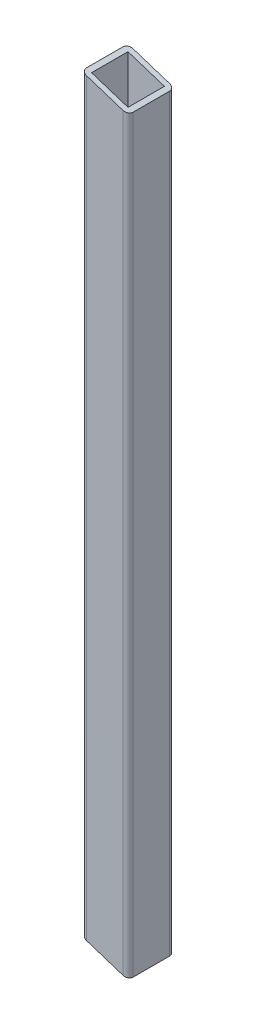
SolidWorks part; units mm, degrees
material "Plain Carbon Steel"
ref_plane "Front Plane" through (0, 0, 0) normal (0, 0, 1) x (1, 0, 0)
ref_plane "Top Plane" through (0, 0, 0) normal (0, 1, 0) x (1, 0, 0)
ref_plane "Right Plane" through (0, 0, 0) normal (1, 0, 0) x (0, 0, -1)
sketch "Sketch1" plane through (0, 0, 0) normal (0, 1, 0) x (1, 0, 0)
  line L1 (2.8, 0) -> (22.8, 0)
  line L2 (0, -2.8) -> (0, -22.8)
  line L3 (2.8, -25.6) -> (22.8, -25.6)
  line L4 (25.6, -2.8) -> (25.6, -22.8)
  arc A0 (22.8, 0) -> (25.6, -2.8) centre (22.8, -2.8) cw
  arc A1 (22.8, -25.6) -> (25.6, -22.8) centre (22.8, -22.8) ccw
  arc A2 (0, -22.8) -> (2.8, -25.6) centre (2.8, -22.8) ccw
  arc A3 (2.8, 0) -> (0, -2.8) centre (2.8, -2.8) ccw
  point P7 (25.6, 0)
  point P10 (25.6, -25.6)
  point P15 (0, 0)
  dimension "D2" = 2.8
  dimension "D1" = 25.6
extrude "Boss-Extrude1" add sketch "Sketch1" along normal blind 420
sketch "Sketch3" plane through (0, 0, 0) normal (0, -1, 0) x (-1, 0, 0)
  line L4 (-2.8, -2.8) -> (-22.8, -2.8)
  line L5 (-2.8, -2.8) -> (-2.8, -22.8)
  line L6 (-2.8, -22.8) -> (-22.8, -22.8)
  line L7 (-22.8, -2.8) -> (-22.8, -22.8)
  line L8 (-2.8, -2.8) -> (-22.8, -22.8) construction
  line L9 (-2.8, -22.8) -> (-22.8, -2.8) construction
  point P6 (-12.8, -12.8)
extrude "Cut-Extrude1" cut sketch "Sketch3" against normal blind 1040.5
ref_plane "Plane1" through (0, 0, 22.8) normal (0, 0, 1) x (1, 0, 0)
sketch "Sketch4" plane through (0, 0, 22.8) normal (0, 0, 1) x (1, 0, 0)
  line L0 (0, 420) -> (25.6, 411.6821)
  line L1 (25.6, 420) -> (25.6, 0) construction
sketch "Sketch5" plane through (0, 0, 22.8) normal (0, 0, 1) x (1, 0, 0)
  line L0 (25.6, 0) -> (0, 8.3179)
  line L1 (0, 420) -> (0, 0) construction
extrude "Cut-Extrude3" cut sketch "Sketch5" against normal through all and the other way through all
extrude "Cut-Extrude4" cut sketch "Sketch4" against normal through all and the other way through all
